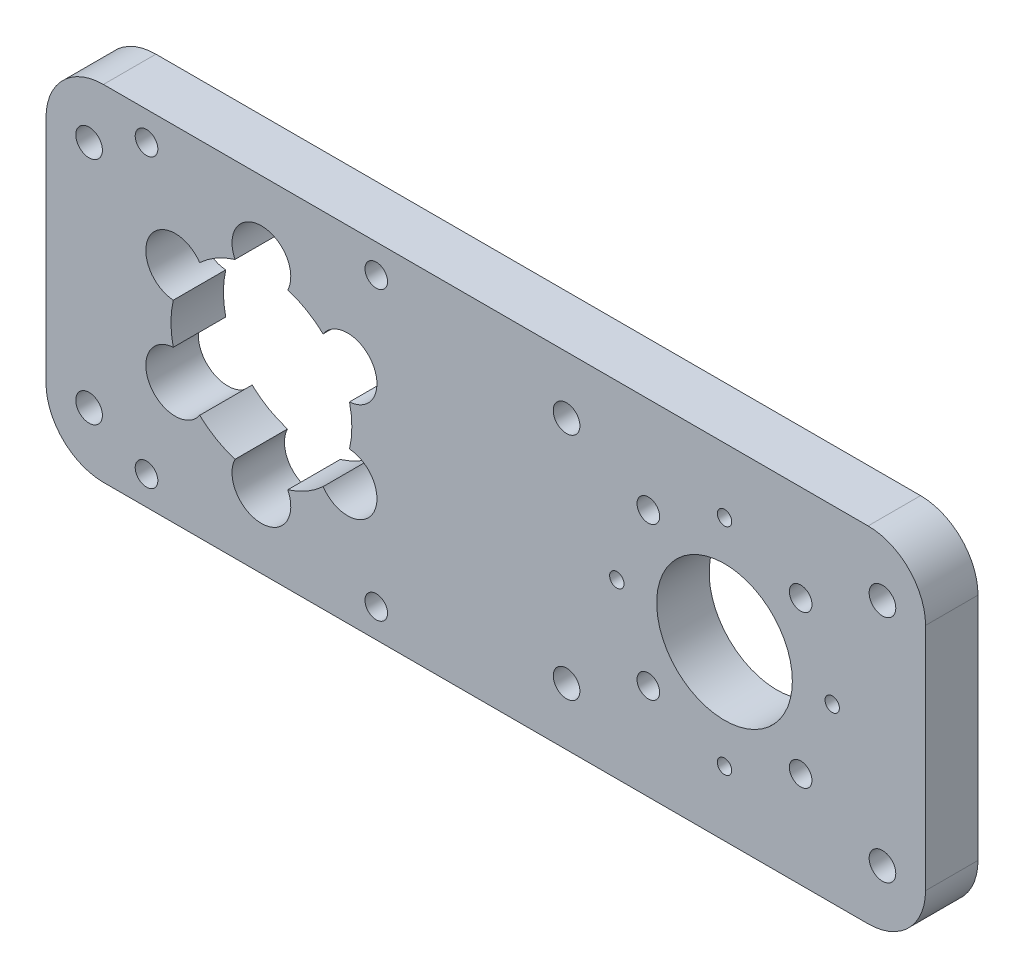
SolidWorks part; units mm, degrees
material "Acrylic (Medium-high impact)"
ref_plane "Front Plane" through (0, 0, 0) normal (0, 0, 1) x (1, 0, 0)
ref_plane "Top Plane" through (0, 0, 0) normal (0, 1, 0) x (1, 0, 0)
ref_plane "Right Plane" through (0, 0, 0) normal (1, 0, 0) x (0, 0, -1)
sketch "Sketch1" plane through (0, 0, 0) normal (0, 0, 1) x (1, 0, 0)
  line L0 (0, 38.1) -> (97.2375, 38.1)
  line L1 (97.2375, 38.1) -> (97.2375, 0)
  line L2 (0, 0) -> (0, 38.1)
  line L3 (97.2375, 0) -> (0, 0)
  line L4 (23.8125, 19.05) -> (0, 19.05) construction
  line L5 (22.7753, 23.7086) -> (71.5569, 34.57) construction
  line L6 (22.7753, 14.3914) -> (71.5569, 3.53) construction
  line L7 (75.0125, 19.05) -> (97.2375, 19.05) construction
  line L14 (75.0125, 0) -> (75.0125, 19.05) construction
  line L25 (75.0125, 19.05) -> (23.8125, 19.05) construction
  arc A0 (22.7753, 23.7086) -> (22.7753, 14.3914) centre (23.8125, 19.05) ccw construction
  arc A1 (71.5569, 3.53) -> (71.5569, 34.57) centre (75.0125, 19.05) ccw construction
  circle A9 centre (75.0125, 19.05) radius 7.5
  circle A14 centre (23.8125, 19.05) radius 10
  dimension "D3" = 51.2
  dimension "D9" = 31.8
  dimension "D16" = 15
  dimension "D24" = 20
  dimension "D8" = 9.5453
  dimension "D1" = 38.1
  dimension "D5" = 23.8125
  dimension "D4" = 22.225
extrude "Boss-Extrude1" add sketch "Sketch1" along normal blind 5.8
sketch "Sketch3" plane through (0, 0, 5.8) normal (0, 0, 1) x (1, 0, 0)
  line L0 (22.7742, 23.7364) -> (71.5786, 34.5492) construction
  line L1 (22.7742, 14.3636) -> (71.5786, 3.5508) construction
  line L20 (23.8125, 19.05) -> (75.0125, 19.05) construction
  line L21 (54.7996, 5.2954) -> (42.3192, 2.9441) construction
  line L22 (51.0917, 7.8277) -> (41.7313, 6.0642)
  line L23 (52.2673, 1.5875) -> (42.907, -0.176)
  arc A0 (22.7742, 23.7364) -> (22.7742, 14.3636) centre (23.8125, 19.05) ccw construction
  arc A1 (71.5786, 3.5508) -> (71.5786, 34.5492) centre (75.0125, 19.05) ccw construction
  circle A2 centre (23.8125, 19.05) radius 15 construction
  circle A8 centre (75.0125, 19.05) radius 15.875 construction
  arc A21 (52.2673, 1.5875) -> (51.0917, 7.8277) centre (51.6795, 4.7076) ccw
  arc A22 (41.7313, 6.0642) -> (42.907, -0.176) centre (42.3192, 2.9441) ccw
  circle A23 centre (51.6795, 4.7076) radius 8.7312 construction
  dimension "D1" = 4.8
  dimension "D2" = 15.875
  dimension "D3" = 6.35
  dimension "D5" = 30
  dimension "D4" = 9.525
hole_wizard "CBORE for M3 SHCS1" positions "Sketch7" profile "Sketch6" counterbore size "M3" standard "ANSI Metric" end condition through all
sketch "Sketch7" plane through (0, 0, 5.8) normal (0, 0, 1) x (1, 0, 0)
  line L32 (23.8125, 19.05) -> (33.3388, 13.55) construction
  line L34 (23.8125, 19.05) -> (23.8125, 8.05) construction
  line L35 (23.8125, 19.05) -> (14.2862, 13.55) construction
  line L36 (23.8125, 19.05) -> (14.2862, 24.55) construction
  line L37 (23.8125, 19.05) -> (23.8125, 30.05) construction
  line L38 (23.8125, 19.05) -> (33.3388, 24.55) construction
  circle A2 centre (23.8125, 19.05) radius 11 construction
  point P112 (33.3388, 13.55)
  point P144 (33.3388, 24.55)
  point P146 (23.8125, 30.05)
  point P148 (14.2862, 24.55)
  point P150 (14.2862, 13.55)
  point P152 (23.8125, 8.05)
  dimension "D1" = 11
  dimension "D2" = 6
sketch "Sketch6" plane through (33.3388, 13.55, 5.8) normal (1, 0, 0) x (0, -1, 0)
  line L0 (0, 0) -> (0, 5.8)
  line L1 (0, 5.8) -> (1.6, 5.8)
  line L3 (1.6, 5.8) -> (1.6, 13)
  line L4 (1.6, 13) -> (3.25, 13)
  line L5 (3.25, 13) -> (3.25, 0)
  line L7 (3.25, 0) -> (0, 0)
  line L11 (0, -6.35) -> (0, 107.95) construction
  dimension "Thru Hole Dia." = 3.2
  dimension "Thru Hole Depth" = 5.8
  dimension "C'Bore Dia." = 6.5
  dimension "C'Bore Depth" = 13
fillet "Fillet1" radius 6.35 4 edges at (0, 0, 2.9) (97.2375, 0, 2.9) (97.2375, 38.1, 2.9) (0, 38.1, 2.9)
hole_wizard "#4 Clearance Hole1" positions "Sketch10" profile "Sketch9" hole size "#4" standard "ANSI Inch"
sketch "Sketch10" plane through (0, 0, 5.8) normal (0, 0, 1) x (1, 0, 0)
  line L9 (4.7625, 6.35) -> (92.475, 6.35) construction
  line L10 (92.475, 6.35) -> (92.475, 31.75) construction
  line L12 (97.2375, 6.35) -> (97.2375, 31.75) construction
  line L13 (4.7625, 31.75) -> (92.475, 31.75) construction
  line L15 (4.7625, 31.75) -> (4.7625, 6.35) construction
  line L17 (4.7625, 19.05) -> (23.8125, 19.05) construction
  line L18 (57.55, 31.75) -> (57.55, 6.35) construction
  line L20 (57.55, 19.05) -> (75.0125, 19.05) construction
  line L21 (75.0125, 19.05) -> (92.475, 19.05) construction
  circle A0 centre (23.8125, 19.05) radius 15 construction
  circle A1 centre (75.0125, 19.05) radius 15.875 construction
  circle A2 centre (23.8125, 19.05) radius 6.35 construction
  point P0 (4.7625, 31.75)
  point P1 (4.7625, 6.35)
  point P5 (92.475, 6.35)
  point P7 (92.475, 31.75)
  point P58 (57.55, 31.75)
  point P60 (57.55, 6.35)
  dimension "D1" = 31.75
  dimension "D2" = 30
  dimension "D3" = 12.7
  dimension "D4" = 19.05
  dimension "D5" = 12.7
  dimension "D7" = 4.7625
sketch "Sketch9" plane through (4.7625, 31.75, 5.8) normal (1, 0, 0) x (0, -1, 0)
  line L0 (0, 0) -> (0, 6.6852)
  line L1 (0, 6.6852) -> (1.4732, 5.8)
  line L2 (1.4732, 5.8) -> (1.4732, 0)
  line L5 (1.4732, 0) -> (0, 0)
  line L10 (0, 6.6852) -> (-1.4732, 5.8) construction
  line L11 (0, -6.35) -> (0, 107.95) construction
  dimension "Hole Dia." = 2.9464
  dimension "Hole Depth" = 5.8
  dimension "Drill Angle" = 118
hole_wizard "M3x0.5 Tapped Hole1" positions "Sketch13" profile "Sketch12" tap size "M3x0.5" standard "ANSI Metric"
sketch "Sketch13" plane through (0, 0, 5.8) normal (0, 0, 1) x (1, 0, 0)
  line L0 (36.5125, 34.925) -> (11.1125, 34.925) construction
  line L1 (11.1125, 34.925) -> (11.1125, 3.175) construction
  line L2 (11.1125, 3.175) -> (36.5125, 3.175) construction
  line L4 (23.8125, 19.05) -> (23.8125, 34.925) construction
  line L6 (23.8125, 19.05) -> (23.8125, 3.175) construction
  point P0 (11.1125, 34.925)
  point P1 (36.5125, 34.925)
  point P3 (36.5125, 3.175)
  point P5 (11.1125, 3.175)
  dimension "D1" = 25.4
  dimension "D2" = 31.75
sketch "Sketch12" plane through (11.1125, 34.925, 5.8) normal (1, 0, 0) x (0, -1, 0)
  line L0 (0, 0) -> (0, 8.2511)
  line L1 (0, 8.2511) -> (1.25, 7.5)
  line L2 (1.25, 7.5) -> (1.25, 0)
  line L5 (1.25, 0) -> (0, 0)
  line L10 (0, 8.2511) -> (-1.25, 7.5) construction
  line L11 (0, -6.35) -> (0, 107.95) construction
  dimension "Tap Drill Dia." = 2.5
  dimension "Tap Drill Depth" = 7.5
  dimension "Drill Angle" = 118
hole_wizard "M3x0.5 Tapped Hole2" positions "Sketch15" profile "Sketch16" tap size "M3x0.5" standard "Ansi Metric"
sketch "Sketch15" plane through (0, 0, 5.8) normal (0, 0, 1) x (1, 0, 0)
  line L0 (75.0125, 19.05) -> (66.5935, 19.05) construction
  line L1 (66.5935, 19.05) -> (66.5935, 27.469) construction
  line L2 (66.5935, 27.469) -> (83.4315, 27.469) construction
  line L3 (83.4315, 27.469) -> (83.4315, 10.631) construction
  line L4 (83.4315, 10.631) -> (66.5935, 10.631) construction
  line L5 (66.5935, 10.631) -> (66.5935, 19.05) construction
  line L7 (75.0125, 19.05) -> (83.4315, 19.05) construction
  line L9 (75.0125, 27.469) -> (75.0125, 19.05) construction
  circle A0 centre (75.0125, 19.05) radius 11.9063 construction
  point P0 (66.5935, 27.469)
  point P1 (83.4315, 27.469)
  point P3 (83.4315, 10.631)
  point P5 (66.5935, 10.631)
  dimension "D1" = 23.8125
sketch "Sketch16" plane through (66.5935, 27.469, 5.8) normal (1, 0, 0) x (0, -1, 0)
  line L0 (0, 0) -> (0, 9.2511)
  line L1 (0, 9.2511) -> (1.25, 8.5)
  line L2 (1.25, 8.5) -> (1.25, 0)
  line L5 (1.25, 0) -> (0, 0)
  line L10 (0, 9.2511) -> (-1.25, 8.5) construction
  line L11 (0, -6.35) -> (0, 107.95) construction
  dimension "Tap Drill Dia." = 2.5
  dimension "Tap Drill Depth" = 8.5
  dimension "Drill Angle" = 118
sketch "Sketch17" plane through (0, 0, 5.8) normal (0, 0, 1) x (1, 0, 0)
  circle A0 centre (63.1063, 19.05) radius 0.7937
  circle A1 centre (75.0125, 7.1438) radius 0.7937
  circle A2 centre (86.9188, 19.05) radius 0.7937
  circle A3 centre (75.0125, 30.9563) radius 0.7937
  circle A4 centre (75.0125, 19.05) radius 11.9063 construction
  dimension "D1" = 1.5875
extrude "Cut-Extrude3" cut sketch "Sketch17" against normal through all
other "Move Face1" [suppressed] parameters "D1"=0.2
